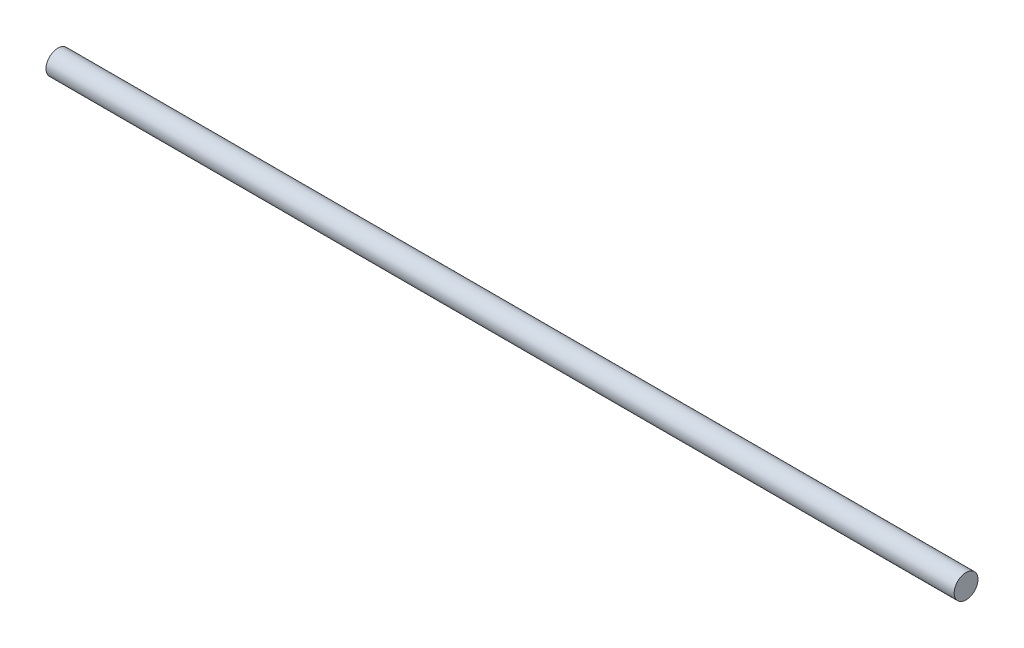
SolidWorks part; units mm, degrees
ref_plane "前视基准面" through (0, 0, 0) normal (0, 0, 1) x (1, 0, 0)
ref_plane "上视基准面" through (0, 0, 0) normal (0, 1, 0) x (1, 0, 0)
ref_plane "右视基准面" through (0, 0, 0) normal (1, 0, 0) x (0, 0, -1)
sketch "草图1" plane through (0, 0, 0) normal (1, 0, 0) x (0, 0, -1)
  circle A0 centre (0, 0) radius 4
  dimension "D1" = 8
extrude "凸台-拉伸1" add sketch "草图1" along normal blind 305
